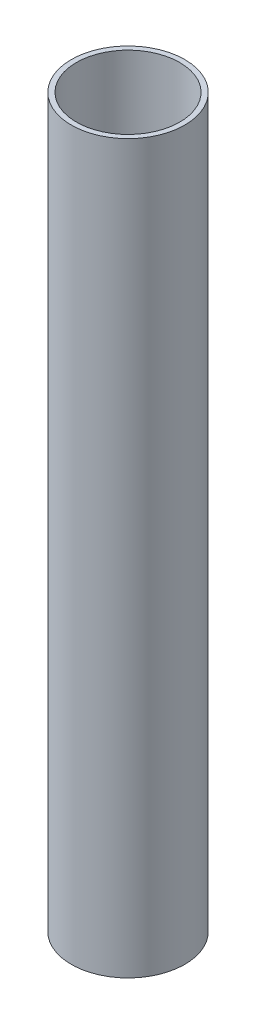
SolidWorks part; units mm, degrees
ref_plane "Front Plane" through (0, 0, 0) normal (0, 0, 1) x (1, 0, 0)
ref_plane "Top Plane" through (0, 0, 0) normal (0, 1, 0) x (1, 0, 0)
ref_plane "Right Plane" through (0, 0, 0) normal (1, 0, 0) x (0, 0, -1)
sketch "Sketch1" plane through (0, 0, 0) normal (0, 0, 1) x (1, 0, 0)
  line L0 (7.9337, 101.6) -> (7.2225, 101.6)
  line L1 (7.2225, 101.6) -> (7.2225, 0)
  line L2 (7.2225, 0) -> (7.9337, 0)
  line L3 (7.9337, 0) -> (7.9337, 101.6)
  line L4 (0, 101.6) -> (0, 0) construction
revolve "Revolve1" add sketch "Sketch1" angle 360 about L4
